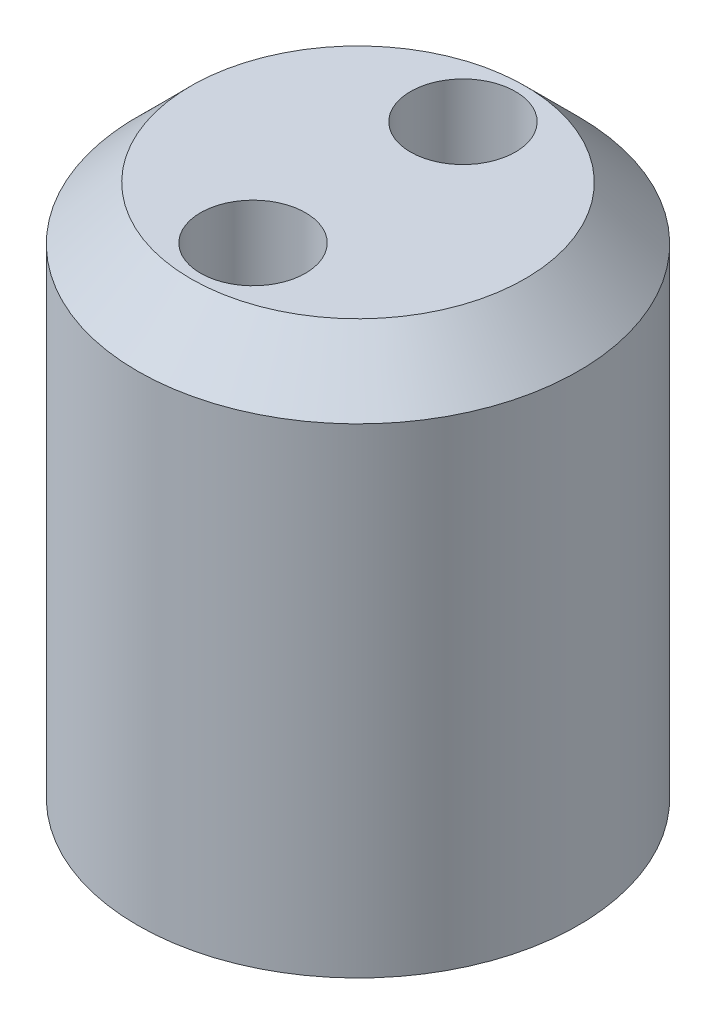
SolidWorks part; units mm, degrees
ref_plane "Front Plane" through (0, 0, 0) normal (0, 0, 1) x (1, 0, 0)
ref_plane "Top Plane" through (0, 0, 0) normal (0, 1, 0) x (1, 0, 0)
ref_plane "Right Plane" through (0, 0, 0) normal (1, 0, 0) x (0, 0, -1)
sketch "Sketch1" plane through (0, 0, 0) normal (0, 1, 0) x (1, 0, 0)
  line L0 (0, -5) -> (0, 5) construction
  circle A0 centre (0, 0) radius 10.5
  circle A2 centre (0, 5) radius 2.5
  circle A3 centre (0, -5) radius 2.5
  dimension "D1" = 21
  dimension "D2" = 5
  dimension "D3" = 10
extrude "Boss-Extrude1" add sketch "Sketch1" along normal blind 25.4
chamfer "Chamfer1" distance 2.54 angle 45 1 edges at (0, 25.4, 10.5)
equation "\"cf_tube_outer_diameter\"= 25mm"
equation "\"cf_tube_inner_diameter\" = 21mm"
equation "\"mid_plate_mid_to_top\" = 100mm"
equation "\"mid_plate_mid_to_bottom\" = 30mm"
equation "\"mid_plate_horizontal_spacing\"=250mm"
equation "\"cf_plate_thickness\" =4mm"
equation "\"mid_tube_length\" = 121mm"
equation "\"D1@Sketch1\"=\"cf_tube_inner_diameter\""
